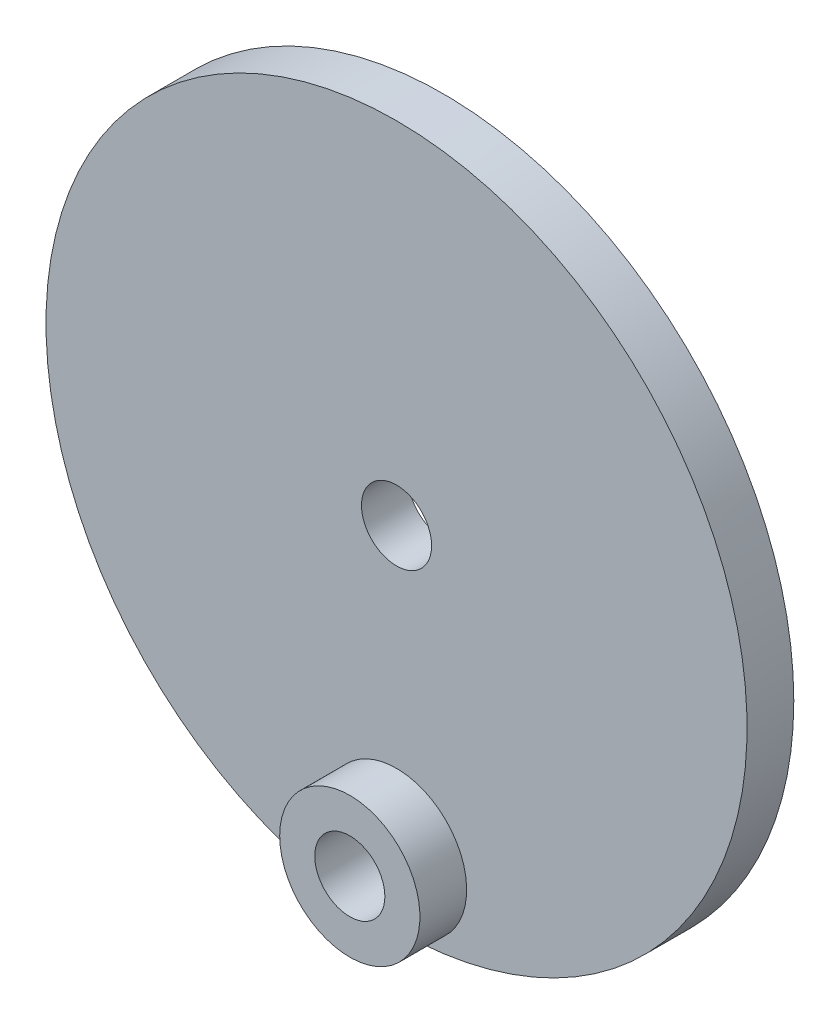
SolidWorks part; units mm, degrees
material "ABS"
ref_plane "Plan de face" through (0, 0, 0) normal (0, 0, 1) x (1, 0, 0)
ref_plane "Plan de dessus" through (0, 0, 0) normal (0, 1, 0) x (1, 0, 0)
ref_plane "Plan de droite" through (0, 0, 0) normal (1, 0, 0) x (0, 0, -1)
sketch "Esquisse1" plane through (0, 0, 0) normal (0, 0, 1) x (1, 0, 0)
  circle A0 centre (0, 0) radius 15
  dimension "D1" = 30
extrude "Boss.-Extru.1" add sketch "Esquisse1" along normal blind 2
sketch "Esquisse2" plane through (0, 0, 2) normal (0, 0, 1) x (1, 0, 0)
  circle A0 centre (0, 0) radius 1.5
  dimension "D1" = 3
extrude "Enlèv. mat.-Extru.1" cut sketch "Esquisse2" against normal blind 3
sketch "Esquisse3" plane through (0, 0, 2) normal (0, 0, 1) x (1, 0, 0)
  circle A0 centre (0, -12) radius 1.5
  circle A1 centre (0, 0) radius 1.5 construction
  dimension "D1" = 3
  dimension "D2" = 12
extrude "Enlèv. mat.-Extru.2" cut sketch "Esquisse3" against normal blind 3
sketch "Esquisse4" plane through (0, 0, 0) normal (0, 0, -1) x (-1, 0, 0)
  circle A0 centre (0, -12) radius 3
  circle A1 centre (0, -12) radius 1.5
  dimension "D1" = 6
  dimension "D2" = 3
extrude "Boss.-Extru.2" add sketch "Esquisse4" against normal blind 4
